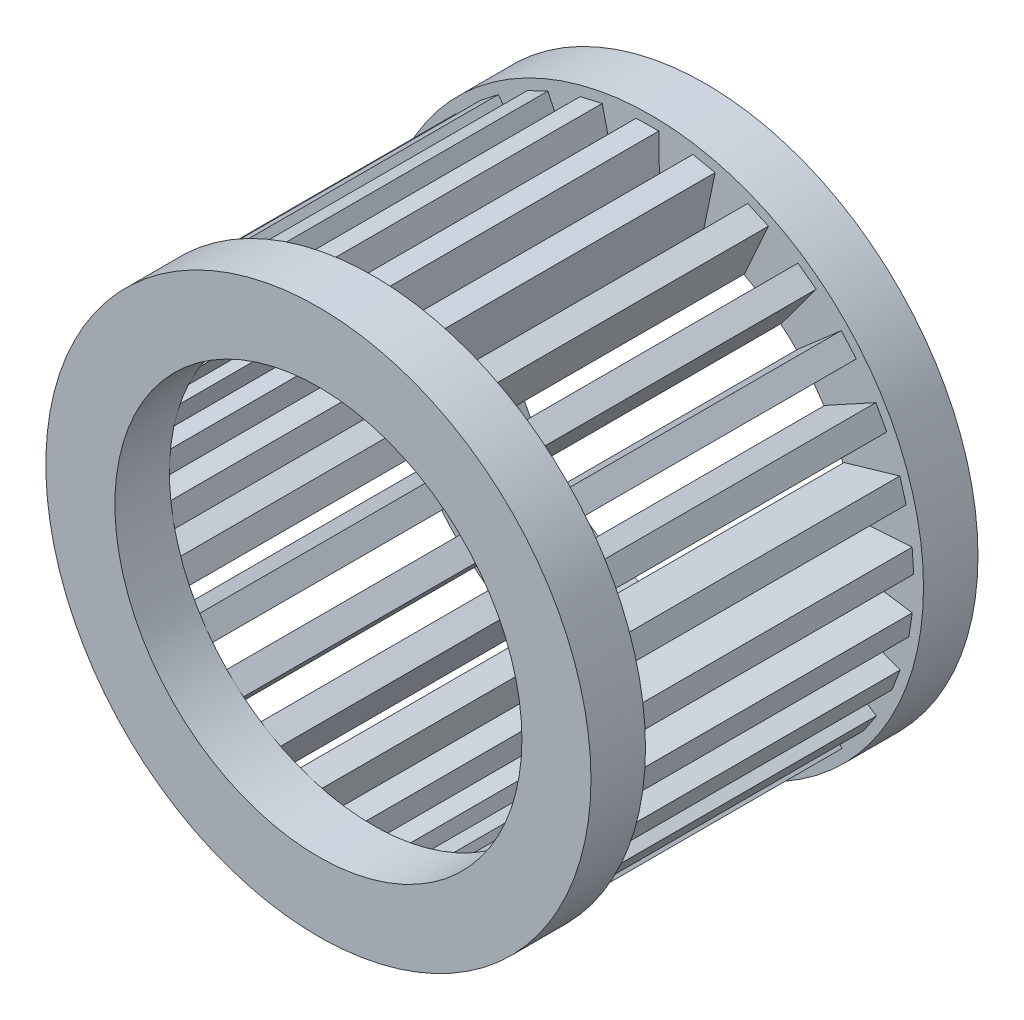
SolidWorks part; units mm, degrees
ref_plane "Спереди" through (0, 0, 0) normal (0, 0, 1) x (1, 0, 0)
ref_plane "Сверху" through (0, 0, 0) normal (0, 1, 0) x (1, 0, 0)
ref_plane "Справа" through (0, 0, 0) normal (1, 0, 0) x (0, 0, -1)
sketch "Эскиз1" plane through (0, 0, 0) normal (0, 0, 1) x (1, 0, 0)
  line L0 (22.5332, 0.2629) -> (28.9187, 0.6924)
  line L1 (28.9187, 0.6924) -> (28.7509, 3.1868)
  line L2 (28.7509, 3.1868) -> (22.3654, 2.7573)
  line L3 (22.3654, 2.7573) -> (22.5332, 0.2629)
  line L4 (21.9498, 5.1007) -> (28.0938, 6.8929)
  line L5 (28.0938, 6.8929) -> (27.3937, 9.2929)
  line L6 (27.3937, 9.2929) -> (21.2498, 7.5007)
  line L7 (21.2498, 7.5007) -> (21.9498, 5.1007)
  line L8 (20.3402, 9.7) -> (25.9552, 12.7711)
  line L9 (25.9552, 12.7711) -> (24.7556, 14.9645)
  line L10 (24.7556, 14.9645) -> (19.1405, 11.8934)
  line L11 (19.1405, 11.8934) -> (20.3402, 9.7)
  line L12 (17.7794, 13.8458) -> (22.603, 18.0521)
  line L13 (22.603, 18.0521) -> (20.9599, 19.9363)
  line L14 (20.9599, 19.9363) -> (16.1363, 15.73)
  line L15 (16.1363, 15.73) -> (17.7794, 13.8458)
  line L16 (14.3873, 17.3441) -> (18.1938, 22.489)
  line L17 (18.1938, 22.489) -> (16.1841, 23.976)
  line L18 (16.1841, 23.976) -> (12.3776, 18.8311)
  line L19 (12.3776, 18.8311) -> (14.3873, 17.3441)
  line L20 (10.3225, 20.0315) -> (12.934, 25.8744)
  line L21 (12.934, 25.8744) -> (10.6516, 26.8945)
  line L22 (10.6516, 26.8945) -> (8.0401, 21.0516)
  line L23 (8.0401, 21.0516) -> (10.3225, 20.0315)
  line L24 (5.7749, 21.7822) -> (7.0694, 28.0499)
  line L25 (7.0694, 28.0499) -> (4.6211, 28.5555)
  line L26 (4.6211, 28.5555) -> (3.3266, 22.2878)
  line L27 (3.3266, 22.2878) -> (5.7749, 21.7822)
  line L28 (0.9574, 22.5143) -> (0.8742, 28.9138)
  line L29 (0.8742, 28.9138) -> (-1.6256, 28.8813)
  line L30 (-1.6256, 28.8813) -> (-1.5424, 22.4818)
  line L31 (-1.5424, 22.4818) -> (0.9574, 22.5143)
  line L32 (-3.9049, 22.1938) -> (-5.3618, 28.4257)
  line L33 (-5.3618, 28.4257) -> (-7.7962, 27.8566)
  line L34 (-7.7962, 27.8566) -> (-6.3393, 21.6247)
  line L35 (-6.3393, 21.6247) -> (-3.9049, 22.1938)
  line L36 (-8.5846, 20.8355) -> (-11.3472, 26.6085)
  line L37 (-11.3472, 26.6085) -> (-13.6023, 25.5294)
  line L38 (-13.6023, 25.5294) -> (-10.8397, 19.7563)
  line L39 (-10.8397, 19.7563) -> (-8.5846, 20.8355)
  line L40 (-12.8629, 18.5029) -> (-16.8019, 23.5471)
  line L41 (-16.8019, 23.5471) -> (-18.7723, 22.0085)
  line L42 (-18.7723, 22.0085) -> (-14.8333, 16.9642)
  line L43 (-14.8333, 16.9642) -> (-12.8629, 18.5029)
  line L44 (-16.5398, 15.3052) -> (-21.4711, 19.3847)
  line L45 (-21.4711, 19.3847) -> (-23.0646, 17.4584)
  line L46 (-23.0646, 17.4584) -> (-18.1333, 13.3789)
  line L47 (-18.1333, 13.3789) -> (-16.5398, 15.3052)
  line L48 (-19.4432, 11.3918) -> (-25.1362, 14.3158)
  line L49 (-25.1362, 14.3158) -> (-26.2784, 12.092)
  line L50 (-26.2784, 12.092) -> (-20.5854, 9.168)
  line L51 (-20.5854, 9.168) -> (-19.4432, 11.3918)
  line L52 (-21.4376, 6.9457) -> (-27.626, 8.5776)
  line L53 (-27.626, 8.5776) -> (-28.2635, 6.1602)
  line L54 (-28.2635, 6.1602) -> (-22.075, 4.5284)
  line L55 (-22.075, 4.5284) -> (-21.4376, 6.9457)
  line L56 (-22.4295, 2.1749) -> (-28.8241, 2.4383)
  line L57 (-28.8241, 2.4383) -> (-28.927, -0.0596)
  line L58 (-28.927, -0.0596) -> (-22.5324, -0.323)
  line L59 (-22.5324, -0.323) -> (-22.4295, 2.1749)
  line L60 (-22.3726, -2.6976) -> (-28.6743, -3.815)
  line L61 (-28.6743, -3.815) -> (-28.2379, -6.2766)
  line L62 (-28.2379, -6.2766) -> (-21.9362, -5.1592)
  line L63 (-21.9362, -5.1592) -> (-22.3726, -2.6976)
  line L64 (-21.2697, -7.444) -> (-27.1838, -9.89)
  line L65 (-27.1838, -9.89) -> (-26.2284, -12.2002)
  line L66 (-26.2284, -12.2002) -> (-20.3142, -9.7542)
  line L67 (-20.3142, -9.7542) -> (-21.2697, -7.444)
  line L68 (-19.1722, -11.8423) -> (-24.4222, -15.5025)
  line L69 (-24.4222, -15.5025) -> (-22.9925, -17.5533)
  line L70 (-22.9925, -17.5533) -> (-17.7424, -13.8931)
  line L71 (-17.7424, -13.8931) -> (-19.1722, -11.8423)
  line L72 (-16.1782, -15.6869) -> (-20.5187, -20.3901)
  line L73 (-20.5187, -20.3901) -> (-18.6815, -22.0856)
  line L74 (-18.6815, -22.0856) -> (-14.341, -17.3824)
  line L75 (-14.341, -17.3824) -> (-16.1782, -15.6869)
  line L76 (-12.4277, -18.798) -> (-15.6557, -24.3243)
  line L77 (-15.6557, -24.3243) -> (-13.497, -25.5852)
  line L78 (-13.497, -25.5852) -> (-10.269, -20.0589)
  line L79 (-10.269, -20.0589) -> (-12.4277, -18.798)
  line L80 (-8.0962, -21.0301) -> (-10.0607, -27.1211)
  line L81 (-10.0607, -27.1211) -> (-7.6814, -27.8885)
  line L82 (-7.6814, -27.8885) -> (-5.7168, -21.7975)
  line L83 (-5.7168, -21.7975) -> (-8.0962, -21.0301)
  line L84 (-3.386, -22.2789) -> (-3.9952, -28.6498)
  line L85 (-3.9952, -28.6498) -> (-1.5066, -28.8878)
  line L86 (-1.5066, -28.8878) -> (-0.8974, -22.5168)
  line L87 (-0.8974, -22.5168) -> (-3.386, -22.2789)
  line L88 (1.4824, -22.4859) -> (2.257, -28.8388)
  line L89 (2.257, -28.8388) -> (4.7387, -28.5362)
  line L90 (4.7387, -28.5362) -> (3.9641, -22.1833)
  line L91 (3.9641, -22.1833) -> (1.4824, -22.4859)
  line L92 (6.2816, -21.6415) -> (8.4038, -27.6794)
  line L93 (8.4038, -27.6794) -> (10.7623, -26.8504)
  line L94 (10.7623, -26.8504) -> (8.6401, -20.8125)
  line L95 (8.6401, -20.8125) -> (6.2816, -21.6415)
  line L96 (10.787, -19.7852) -> (14.1575, -25.2257)
  line L97 (14.1575, -25.2257) -> (16.2828, -23.9091)
  line L98 (16.2828, -23.9091) -> (12.9122, -18.4686)
  line L99 (12.9122, -18.4686) -> (10.787, -19.7852)
  line L100 (14.788, -17.0037) -> (19.2493, -21.5925)
  line L101 (19.2493, -21.5925) -> (21.0418, -19.8498)
  line L102 (21.0418, -19.8498) -> (16.5805, -15.261)
  line L103 (16.5805, -15.261) -> (14.788, -17.0037)
  line L104 (18.0976, -13.4272) -> (23.441, -16.9496)
  line L105 (23.441, -16.9496) -> (24.817, -14.8623)
  line L106 (24.817, -14.8623) -> (19.4735, -11.3399)
  line L107 (19.4735, -11.3399) -> (18.0976, -13.4272)
  line L108 (20.5609, -9.2228) -> (26.5367, -11.5142)
  line L109 (26.5367, -11.5142) -> (27.4318, -9.18)
  line L110 (27.4318, -9.18) -> (21.456, -6.8886)
  line L111 (21.456, -6.8886) -> (20.5609, -9.2228)
  line L112 (22.0629, -4.5872) -> (28.3915, -5.5404)
  line L113 (28.3915, -5.5404) -> (28.7638, -3.0683)
  line L114 (28.7638, -3.0683) -> (22.4352, -2.1151)
  line L115 (22.4352, -2.1151) -> (22.0629, -4.5872)
extrude "Bars" add sketch "Эскиз1" along normal blind 30.8 from offset 15.4 separate body
sketch "Эскиз2" plane through (0, 0, 0) normal (0, 0, 1) x (1, 0, 0)
  circle A0 centre (0, 0) radius 30
  circle A1 centre (0, 0) radius 22.4
extrude "End_ring_front" add sketch "Эскиз2" along normal blind 6 from offset 15.3
sketch "Эскиз3" plane through (0, 0, 0) normal (0, 0, 1) x (1, 0, 0)
  circle A0 centre (0, 0) radius 30
  circle A1 centre (0, 0) radius 22.4
extrude "End_ring_rear" add sketch "Эскиз3" along normal blind 6 from offset 21.3
